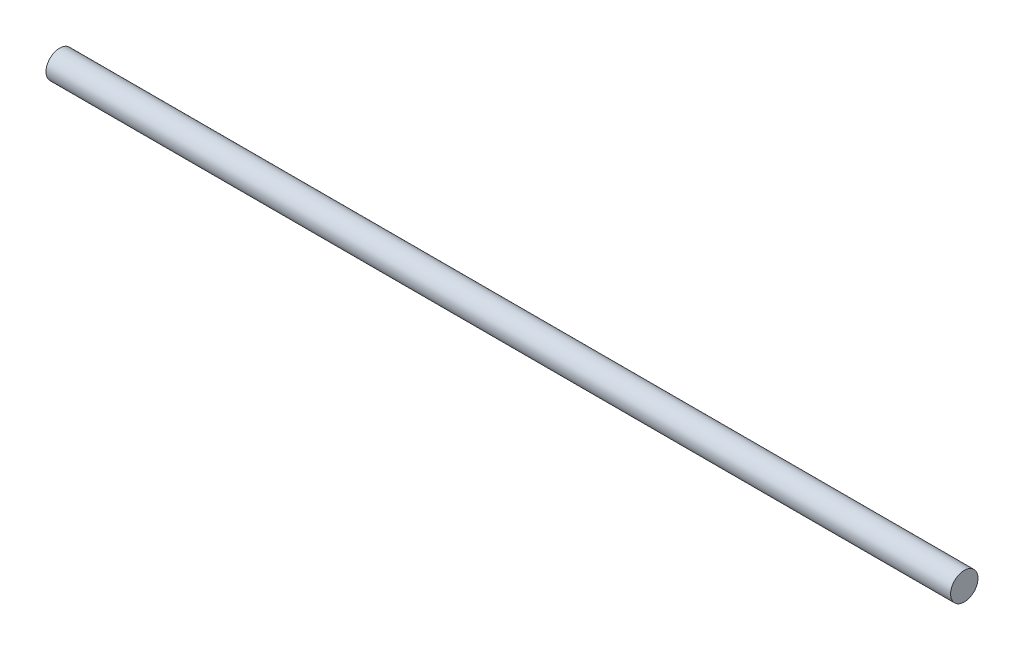
SolidWorks part; units mm, degrees
ref_plane "Front Plane" through (0, 0, 0) normal (0, 0, 1) x (1, 0, 0)
ref_plane "Top Plane" through (0, 0, 0) normal (0, 1, 0) x (1, 0, 0)
ref_plane "Right Plane" through (0, 0, 0) normal (1, 0, 0) x (0, 0, -1)
sketch "Sketch2" plane through (0, 0, 0) normal (1, 0, 0) x (0, 0, -1)
  circle A0 centre (0, 0) radius 3.175
  dimension "D1" = 6.35
extrude "Boss-Extrude1" add sketch "Sketch2" along normal blind 209.55
